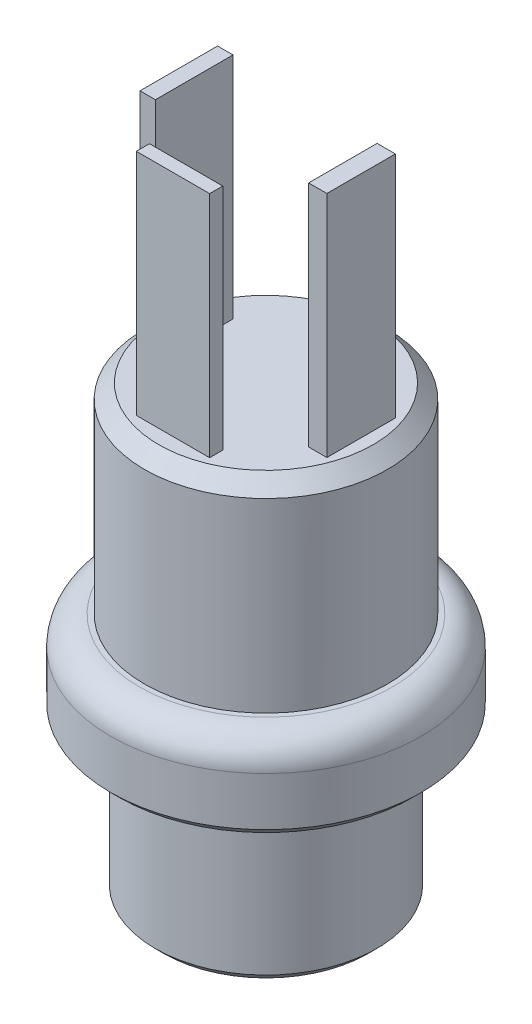
SolidWorks part; units mm, degrees
ref_plane "Alzado" through (0, 0, 0) normal (0, 0, 1) x (1, 0, 0)
ref_plane "Planta" through (0, 0, 0) normal (0, 1, 0) x (1, 0, 0)
ref_plane "Vista lateral" through (0, 0, 0) normal (1, 0, 0) x (0, 0, -1)
sketch "Croquis1" plane through (0, 0, 0) normal (0, 0, 1) x (1, 0, 0)
  line L0 (0, 0) -> (1, 0)
  line L1 (1, 0) -> (1, 6)
  line L2 (1, 6) -> (2.75, 6)
  line L3 (2.75, 6) -> (2.75, -2.5)
  line L4 (2.75, -2.5) -> (3.875, -2.5)
  line L5 (3.875, -2.5) -> (3.875, 3)
  line L6 (3.875, 3) -> (5.425, 3)
  line L7 (5.425, 3) -> (5.425, 6)
  line L8 (5.425, 6) -> (4.25, 6)
  line L9 (4.25, 6) -> (4.25, 13)
  line L10 (4.25, 13) -> (0, 13)
  line L11 (0, 13) -> (0, 0)
  line L12 (0, 0) -> (0, -15761.1662) construction
  dimension "D1" = 2
  dimension "D2" = 5.5
  dimension "D3" = 2.5
  dimension "D4" = 8.5
  dimension "D5" = 5.5
  dimension "D6" = 3
  dimension "D7" = 7.75
  dimension "D8" = 10.85
  dimension "D9" = 8.5
  dimension "D10" = 7
revolve "Revolución1" add sketch "Croquis1" angle 360 about L12
fillet "Redondeo1" radius 1 1 edges at (0, 0, 1)
fillet "Redondeo2" radius 1 1 edges at (0, 6, 5.425)
chamfer "Chaflán1" distance 0.3 angle 45 3 edges at (0, -2.5, 3.875) (0, -2.5, 2.75) (0, 3, 5.425)
chamfer "Chaflán2" distance 0.5 angle 45 1 edges at (0, 13, 4.25)
sketch "Croquis2" plane through (0, 13, 0) normal (0, 1, 0) x (1, 0, 0)
  line L1 (1.2825, -3.2535) -> (-1.2825, -3.2535)
  line L2 (1.2825, -3.2535) -> (1.2825, -2.7945)
  line L3 (1.2825, -2.7945) -> (-1.2825, -2.7945)
  line L4 (-1.2825, -3.2535) -> (-1.2825, -2.7945)
  line L5 (0, -2.7945) -> (0, -3.2535) construction
  line L6 (1.2825, -3.024) -> (-1.2825, -3.024) construction
  line L7 (3.3284, -1.1976) -> (2.6897, -1.1976)
  line L8 (3.3284, -1.1976) -> (3.3284, 1.1976)
  line L9 (3.3284, 1.1976) -> (2.6897, 1.1976)
  line L10 (2.6897, -1.1976) -> (2.6897, 1.1976)
  line L11 (3.009, 1.1976) -> (3.009, -1.1976) construction
  line L12 (3.3284, 0) -> (2.6897, 0) construction
  line L13 (-2.51, -1.3573) -> (-3.0489, -1.3573)
  line L14 (-2.51, -1.3573) -> (-2.51, 1.3573)
  line L15 (-2.51, 1.3573) -> (-3.0489, 1.3573)
  line L16 (-3.0489, -1.3573) -> (-3.0489, 1.3573)
  line L17 (-2.7795, 1.3573) -> (-2.7795, -1.3573) construction
  line L18 (-2.51, 0) -> (-3.0489, 0) construction
  point P0 (0, -3.024)
  point P4 (3.009, 0)
  point P11 (-2.7795, 0)
extrude "Saliente-Extruir1" add sketch "Croquis2" along normal blind 8
